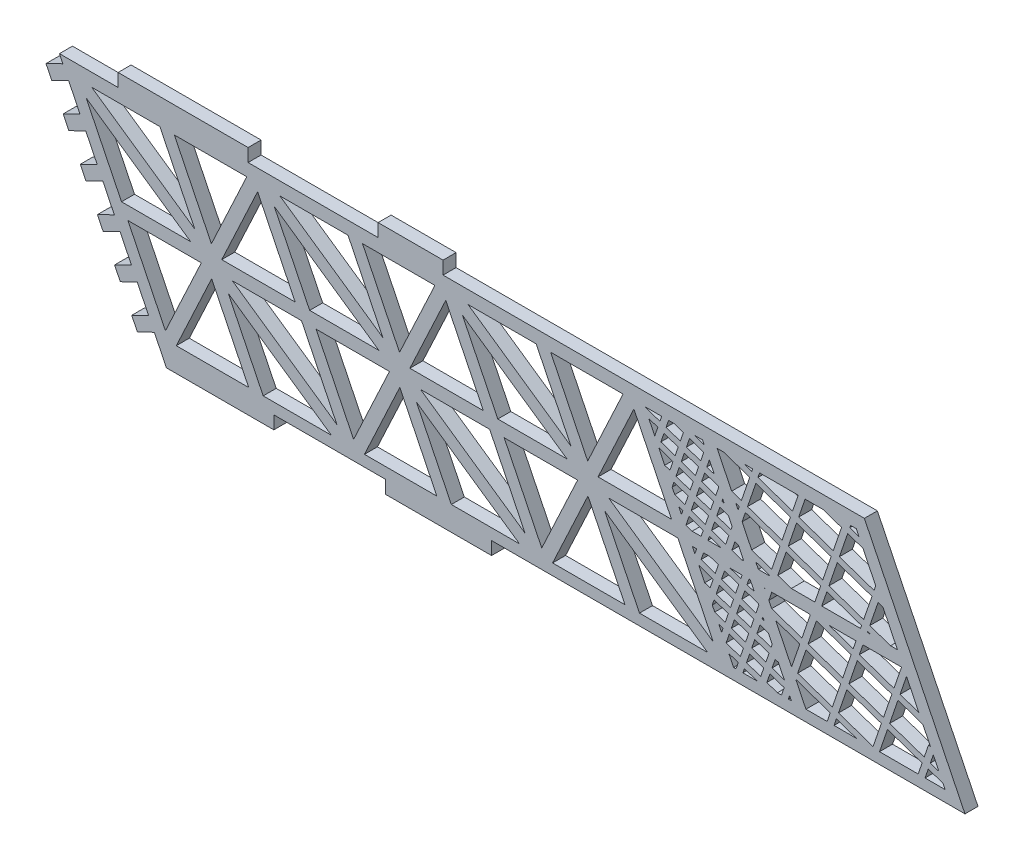
SolidWorks part; units mm, degrees
ref_plane "Front Plane" through (0, 0, 0) normal (0, 0, 1) x (1, 0, 0)
ref_plane "Top Plane" through (0, 0, 0) normal (0, 1, 0) x (1, 0, 0)
ref_plane "Right Plane" through (0, 0, 0) normal (1, 0, 0) x (0, 0, -1)
sketch "Sketch1" plane through (0, 0, 0) normal (0, 0, 1) x (1, 0, 0)
  line L2842 (449.5996, 291) -> (458.5139, 291)
  line L2843 (458.5139, 291) -> (457.1963, 287.1567)
  line L2844 (457.1963, 287.1567) -> (449.2194, 289.8912)
  line L2845 (449.2194, 289.8912) -> (449.5996, 291)
  line L2846 (448.733, 288.4723) -> (456.7099, 285.7377)
  line L2847 (456.7099, 285.7377) -> (454.7887, 280.1333)
  line L2848 (454.7887, 280.1333) -> (446.8118, 282.8678)
  line L2849 (446.8118, 282.8678) -> (448.733, 288.4723)
  line L2850 (444.6261, 281.1177) -> (444.0888, 282.2156)
  line L2851 (444.0888, 282.2156) -> (444.9064, 281.9353)
  line L2852 (444.9064, 281.9353) -> (444.6261, 281.1177)
  line L2853 (445.3928, 283.3542) -> (443.1563, 284.1209)
  line L2854 (443.1563, 284.1209) -> (439.7896, 291)
  line L2855 (439.7896, 291) -> (441.3594, 291)
  line L2856 (441.3594, 291) -> (447.3141, 288.9587)
  line L2857 (447.3141, 288.9587) -> (445.3928, 283.3542)
  line L2858 (448.0139, 291) -> (445.985, 291)
  line L2859 (445.985, 291) -> (447.8005, 290.3776)
  line L2860 (447.8005, 290.3776) -> (448.0139, 291)
  line L2861 (454.3022, 278.7143) -> (452.381, 273.1099)
  line L2862 (452.381, 273.1099) -> (447.772, 274.6898)
  line L2863 (447.772, 274.6898) -> (445.5587, 279.2124)
  line L2864 (445.5587, 279.2124) -> (446.3253, 281.4489)
  line L2865 (446.3253, 281.4489) -> (454.3022, 278.7143)
  line L2866 (478.1923, 256.4128) -> (470.2154, 259.1473)
  line L2867 (470.2154, 259.1473) -> (472.1367, 264.7518)
  line L2868 (472.1367, 264.7518) -> (480.1136, 262.0172)
  line L2869 (480.1136, 262.0172) -> (478.1923, 256.4128)
  line L2870 (480.6, 263.4362) -> (472.6231, 266.1707)
  line L2871 (472.6231, 266.1707) -> (473.4401, 268.5541)
  line L2872 (473.4401, 268.5541) -> (482.3544, 268.5541)
  line L2873 (482.3544, 268.5541) -> (480.6, 263.4362)
  line L2874 (483.5065, 267.289) -> (486.3582, 261.4622)
  line L2875 (486.3582, 261.4622) -> (482.0189, 262.9497)
  line L2876 (482.0189, 262.9497) -> (483.5065, 267.289)
  line L2877 (487.2907, 259.5568) -> (489.0579, 255.9461)
  line L2878 (489.0579, 255.9461) -> (488.5876, 256.1073)
  line L2879 (488.5876, 256.1073) -> (487.5881, 253.1918)
  line L2880 (487.5881, 253.1918) -> (479.6112, 255.9263)
  line L2881 (479.6112, 255.9263) -> (481.5325, 261.5308)
  line L2882 (481.5325, 261.5308) -> (487.2907, 259.5568)
  line L2883 (487.1017, 251.7729) -> (486.1882, 249.1082)
  line L2884 (486.1882, 249.1082) -> (477.2739, 249.1082)
  line L2885 (477.2739, 249.1082) -> (479.1248, 254.5074)
  line L2886 (479.1248, 254.5074) -> (487.1017, 251.7729)
  line L2887 (475.7846, 249.3894) -> (467.8077, 252.1239)
  line L2888 (467.8077, 252.1239) -> (469.729, 257.7284)
  line L2889 (469.729, 257.7284) -> (477.7059, 254.9938)
  line L2890 (477.7059, 254.9938) -> (475.7846, 249.3894)
  line L2891 (474.5443, 271.7752) -> (475.1893, 271.5541)
  line L2892 (475.1893, 271.5541) -> (474.4686, 271.5541)
  line L2893 (474.4686, 271.5541) -> (474.5443, 271.7752)
  line L2894 (476.952, 278.7986) -> (478.0593, 278.419)
  line L2895 (478.0593, 278.419) -> (481.4191, 271.5541)
  line L2896 (481.4191, 271.5541) -> (479.8149, 271.5541)
  line L2897 (479.8149, 271.5541) -> (475.0308, 273.1941)
  line L2898 (475.0308, 273.1941) -> (476.952, 278.7986)
  line L2899 (473.6118, 273.6805) -> (465.6034, 276.4259)
  line L2900 (465.6034, 276.4259) -> (467.5247, 282.0303)
  line L2901 (467.5247, 282.0303) -> (475.5331, 279.285)
  line L2902 (475.5331, 279.285) -> (473.6118, 273.6805)
  line L2903 (472.8829, 271.5541) -> (463.9333, 271.5541)
  line L2904 (463.9333, 271.5541) -> (465.117, 275.0069)
  line L2905 (465.117, 275.0069) -> (473.1254, 272.2616)
  line L2906 (473.1254, 272.2616) -> (472.8829, 271.5541)
  line L2907 (471.2042, 266.6571) -> (465.6706, 268.5541)
  line L2908 (465.6706, 268.5541) -> (471.8544, 268.5541)
  line L2909 (471.8544, 268.5541) -> (471.2042, 266.6571)
  line L2910 (468.7965, 259.6337) -> (460.7881, 262.3791)
  line L2911 (460.7881, 262.3791) -> (462.7093, 267.9835)
  line L2912 (462.7093, 267.9835) -> (470.7177, 265.2382)
  line L2913 (470.7177, 265.2382) -> (468.7965, 259.6337)
  line L2914 (466.3888, 252.6103) -> (458.3804, 255.3557)
  line L2915 (458.3804, 255.3557) -> (460.3016, 260.9601)
  line L2916 (460.3016, 260.9601) -> (468.3101, 258.2148)
  line L2917 (468.3101, 258.2148) -> (466.3888, 252.6103)
  line L2918 (476.3991, 281.8112) -> (473.4436, 287.85)
  line L2919 (473.4436, 287.85) -> (469.9324, 289.0537)
  line L2920 (469.9324, 289.0537) -> (468.0111, 283.4493)
  line L2921 (468.0111, 283.4493) -> (476.0195, 280.7039)
  line L2922 (476.0195, 280.7039) -> (476.3991, 281.8112)
  line L2923 (455.7212, 278.2279) -> (463.6981, 275.4934)
  line L2924 (463.6981, 275.4934) -> (462.3476, 271.5541)
  line L2925 (462.3476, 271.5541) -> (456.9194, 271.5541)
  line L2926 (456.9194, 271.5541) -> (453.7999, 272.6234)
  line L2927 (453.7999, 272.6234) -> (455.7212, 278.2279)
  line L2928 (458.1288, 285.2513) -> (466.1057, 282.5168)
  line L2929 (466.1057, 282.5168) -> (464.1845, 276.9123)
  line L2930 (464.1845, 276.9123) -> (456.2076, 279.6468)
  line L2931 (456.2076, 279.6468) -> (458.1288, 285.2513)
  line L2932 (460.0996, 291) -> (464.2549, 291)
  line L2933 (464.2549, 291) -> (468.5134, 289.5401)
  line L2934 (468.5134, 289.5401) -> (466.5922, 283.9357)
  line L2935 (466.5922, 283.9357) -> (458.6153, 286.6702)
  line L2936 (458.6153, 286.6702) -> (460.0996, 291)
  line L2937 (451.8476, 271.5541) -> (449.3067, 271.5541)
  line L2938 (449.3067, 271.5541) -> (448.7046, 272.7845)
  line L2939 (448.7046, 272.7845) -> (451.8946, 271.6909)
  line L2940 (451.8946, 271.6909) -> (451.8476, 271.5541)
  line L2941 (450.801, 268.5009) -> (450.775, 268.5541)
  line L2942 (450.775, 268.5541) -> (450.8192, 268.5541)
  line L2943 (450.8192, 268.5541) -> (450.801, 268.5009)
  line L2944 (470.5996, 291) -> (471.9019, 291)
  line L2945 (471.9019, 291) -> (472.5111, 289.7554)
  line L2946 (472.5111, 289.7554) -> (470.4188, 290.4727)
  line L2947 (470.4188, 290.4727) -> (470.5996, 291)
  line L2948 (469.0139, 291) -> (468.8805, 291)
  line L2949 (468.8805, 291) -> (468.9998, 290.9591)
  line L2950 (468.9998, 290.9591) -> (469.0139, 291)
  line L2951 (461.045, 268.5541) -> (461.2904, 268.47)
  line L2952 (461.2904, 268.47) -> (459.3691, 262.8655)
  line L2953 (459.3691, 262.8655) -> (452.3878, 265.2588)
  line L2954 (452.3878, 265.2588) -> (451.7335, 266.5956)
  line L2955 (451.7335, 266.5956) -> (452.4049, 268.5541)
  line L2956 (452.4049, 268.5541) -> (461.045, 268.5541)
  line L2957 (456.9759, 255.8841) -> (453.3203, 263.3534)
  line L2958 (453.3203, 263.3534) -> (458.8827, 261.4466)
  line L2959 (458.8827, 261.4466) -> (456.9759, 255.8841)
  line L2960 (471.9794, 249.1082) -> (466.7739, 249.1082)
  line L2961 (466.7739, 249.1082) -> (467.3213, 250.705)
  line L2962 (467.3213, 250.705) -> (471.9794, 249.1082)
  line L2963 (460.2921, 249.1082) -> (457.936, 253.9223)
  line L2964 (457.936, 253.9223) -> (465.9024, 251.1914)
  line L2965 (465.9024, 251.1914) -> (465.1882, 249.1082)
  line L2966 (465.1882, 249.1082) -> (460.2921, 249.1082)
  line L2967 (490.9739, 252.0311) -> (489.0071, 252.7054)
  line L2968 (489.0071, 252.7054) -> (489.6813, 254.6723)
  line L2969 (489.6813, 254.6723) -> (490.9739, 252.0311)
  line L2970 (491.9065, 250.1258) -> (492.4045, 249.1082)
  line L2971 (492.4045, 249.1082) -> (487.7739, 249.1082)
  line L2972 (487.7739, 249.1082) -> (488.5206, 251.2864)
  line L2973 (488.5206, 251.2864) -> (491.9065, 250.1258)
  line L2974 (429.6088, 283.255) -> (428.8914, 281.1623)
  line L2975 (428.8914, 281.1623) -> (427.7052, 281.5689)
  line L2976 (427.7052, 281.5689) -> (426.3299, 284.3791)
  line L2977 (426.3299, 284.3791) -> (429.6088, 283.255)
  line L2978 (427.5337, 287.8908) -> (430.8127, 286.7667)
  line L2979 (430.8127, 286.7667) -> (430.0952, 284.674)
  line L2980 (430.0952, 284.674) -> (426.8163, 285.798)
  line L2981 (426.8163, 285.798) -> (427.5337, 287.8908)
  line L2982 (428.5996, 291) -> (429.9116, 291)
  line L2983 (429.9116, 291) -> (432.0165, 290.2784)
  line L2984 (432.0165, 290.2784) -> (431.2991, 288.1857)
  line L2985 (431.2991, 288.1857) -> (428.0201, 289.3097)
  line L2986 (428.0201, 289.3097) -> (428.5996, 291)
  line L2987 (427.0139, 291) -> (423.0895, 291)
  line L2988 (423.0895, 291) -> (426.6012, 289.7962)
  line L2989 (426.6012, 289.7962) -> (427.0139, 291)
  line L2990 (425.3973, 286.2845) -> (424.022, 289.0946)
  line L2991 (424.022, 289.0946) -> (426.1148, 288.3772)
  line L2992 (426.1148, 288.3772) -> (425.3973, 286.2845)
  line L2993 (429.2666, 271.5541) -> (420.5964, 289.2694)
  line L2994 (420.5964, 289.2694) -> (412.3173, 271.5541)
  line L2995 (412.3173, 271.5541) -> (429.2666, 271.5541)
  line L2996 (429.8239, 279.2569) -> (433.1029, 278.1329)
  line L2997 (433.1029, 278.1329) -> (432.3855, 276.0401)
  line L2998 (432.3855, 276.0401) -> (430.0131, 276.8534)
  line L2999 (430.0131, 276.8534) -> (429.4173, 278.0707)
  line L3000 (429.4173, 278.0707) -> (429.8239, 279.2569)
  line L3001 (431.0278, 282.7686) -> (434.3067, 281.6446)
  line L3002 (434.3067, 281.6446) -> (433.5893, 279.5518)
  line L3003 (433.5893, 279.5518) -> (430.3104, 280.6759)
  line L3004 (430.3104, 280.6759) -> (431.0278, 282.7686)
  line L3005 (432.2316, 286.2803) -> (435.5106, 285.1563)
  line L3006 (435.5106, 285.1563) -> (434.7932, 283.0635)
  line L3007 (434.7932, 283.0635) -> (431.5142, 284.1876)
  line L3008 (431.5142, 284.1876) -> (432.2316, 286.2803)
  line L3009 (433.4354, 289.792) -> (436.7144, 288.668)
  line L3010 (436.7144, 288.668) -> (435.997, 286.5752)
  line L3011 (435.997, 286.5752) -> (432.718, 287.6993)
  line L3012 (432.718, 287.6993) -> (433.4354, 289.792)
  line L3013 (433.318, 274.1347) -> (436.597, 273.0107)
  line L3014 (436.597, 273.0107) -> (436.0976, 271.5541)
  line L3015 (436.0976, 271.5541) -> (434.0238, 271.5541)
  line L3016 (434.0238, 271.5541) -> (432.6006, 272.042)
  line L3017 (432.6006, 272.042) -> (433.318, 274.1347)
  line L3018 (434.5218, 277.6464) -> (437.8008, 276.5224)
  line L3019 (437.8008, 276.5224) -> (437.0834, 274.4296)
  line L3020 (437.0834, 274.4296) -> (433.8044, 275.5537)
  line L3021 (433.8044, 275.5537) -> (434.5218, 277.6464)
  line L3022 (435.7257, 281.1581) -> (439.0047, 280.0341)
  line L3023 (439.0047, 280.0341) -> (438.2872, 277.9413)
  line L3024 (438.2872, 277.9413) -> (435.0083, 279.0654)
  line L3025 (435.0083, 279.0654) -> (435.7257, 281.1581)
  line L3026 (436.9295, 284.6698) -> (440.0755, 283.5914)
  line L3027 (440.0755, 283.5914) -> (440.1629, 283.4128)
  line L3028 (440.1629, 283.4128) -> (439.4911, 281.453)
  line L3029 (439.4911, 281.453) -> (436.2121, 282.5771)
  line L3030 (436.2121, 282.5771) -> (436.9295, 284.6698)
  line L3031 (438.008, 287.8158) -> (439.143, 285.4967)
  line L3032 (439.143, 285.4967) -> (437.4159, 286.0888)
  line L3033 (437.4159, 286.0888) -> (438.008, 287.8158)
  line L3034 (431.5722, 273.6677) -> (430.9456, 274.948)
  line L3035 (430.9456, 274.948) -> (431.8991, 274.6212)
  line L3036 (431.8991, 274.6212) -> (431.5722, 273.6677)
  line L3037 (438.9029, 251.8647) -> (430.7348, 268.5541)
  line L3038 (430.7348, 268.5541) -> (414.7672, 268.5541)
  line L3039 (414.7672, 268.5541) -> (438.9029, 251.8647)
  line L3040 (435.6082, 265.5009) -> (438.8872, 264.3768)
  line L3041 (438.8872, 264.3768) -> (438.1698, 262.284)
  line L3042 (438.1698, 262.284) -> (436.9366, 262.7068)
  line L3043 (436.9366, 262.7068) -> (435.5921, 265.4539)
  line L3044 (435.5921, 265.4539) -> (435.6082, 265.5009)
  line L3045 (436.6549, 268.5541) -> (438.1495, 268.5541)
  line L3046 (438.1495, 268.5541) -> (440.091, 267.8885)
  line L3047 (440.091, 267.8885) -> (439.3736, 265.7957)
  line L3048 (439.3736, 265.7957) -> (436.0947, 266.9198)
  line L3049 (436.0947, 266.9198) -> (436.6549, 268.5541)
  line L3050 (438.0159, 272.5243) -> (440.846, 271.5541)
  line L3051 (440.846, 271.5541) -> (437.6833, 271.5541)
  line L3052 (437.6833, 271.5541) -> (438.0159, 272.5243)
  line L3053 (439.2198, 276.036) -> (442.4987, 274.9119)
  line L3054 (442.4987, 274.9119) -> (441.7813, 272.8191)
  line L3055 (441.7813, 272.8191) -> (438.5023, 273.9432)
  line L3056 (438.5023, 273.9432) -> (439.2198, 276.036)
  line L3057 (440.4236, 279.5477) -> (442.3833, 278.8758)
  line L3058 (442.3833, 278.8758) -> (443.2503, 277.1044)
  line L3059 (443.2503, 277.1044) -> (442.9852, 276.3308)
  line L3060 (442.9852, 276.3308) -> (439.7062, 277.4549)
  line L3061 (439.7062, 277.4549) -> (440.4236, 279.5477)
  line L3062 (441.0954, 281.5074) -> (441.4508, 280.7812)
  line L3063 (441.4508, 280.7812) -> (440.91, 280.9666)
  line L3064 (440.91, 280.9666) -> (441.0954, 281.5074)
  line L3065 (434.6757, 267.4062) -> (434.6288, 267.4223)
  line L3066 (434.6288, 267.4223) -> (434.0749, 268.5541)
  line L3067 (434.0749, 268.5541) -> (435.0692, 268.5541)
  line L3068 (435.0692, 268.5541) -> (434.6757, 267.4062)
  line L3069 (439.1023, 260.3787) -> (442.3813, 259.2546)
  line L3070 (442.3813, 259.2546) -> (441.6639, 257.1619)
  line L3071 (441.6639, 257.1619) -> (439.2445, 257.9912)
  line L3072 (439.2445, 257.9912) -> (438.6796, 259.1455)
  line L3073 (438.6796, 259.1455) -> (439.1023, 260.3787)
  line L3074 (440.3062, 263.8904) -> (443.5851, 262.7663)
  line L3075 (443.5851, 262.7663) -> (442.8677, 260.6736)
  line L3076 (442.8677, 260.6736) -> (439.5887, 261.7976)
  line L3077 (439.5887, 261.7976) -> (440.3062, 263.8904)
  line L3078 (441.51, 267.4021) -> (444.789, 266.278)
  line L3079 (444.789, 266.278) -> (444.0715, 264.1853)
  line L3080 (444.0715, 264.1853) -> (440.7926, 265.3093)
  line L3081 (440.7926, 265.3093) -> (441.51, 267.4021)
  line L3082 (443.9177, 274.4255) -> (444.6912, 274.1603)
  line L3083 (444.6912, 274.1603) -> (445.9667, 271.5541)
  line L3084 (445.9667, 271.5541) -> (445.4716, 271.5541)
  line L3085 (445.4716, 271.5541) -> (443.2003, 272.3327)
  line L3086 (443.2003, 272.3327) -> (443.9177, 274.4255)
  line L3087 (442.5964, 255.2565) -> (445.8754, 254.1324)
  line L3088 (445.8754, 254.1324) -> (445.1579, 252.0397)
  line L3089 (445.1579, 252.0397) -> (441.879, 253.1637)
  line L3090 (441.879, 253.1637) -> (442.5964, 255.2565)
  line L3091 (443.8002, 258.7682) -> (447.0792, 257.6441)
  line L3092 (447.0792, 257.6441) -> (446.3618, 255.5514)
  line L3093 (446.3618, 255.5514) -> (443.0828, 256.6754)
  line L3094 (443.0828, 256.6754) -> (443.8002, 258.7682)
  line L3095 (445.0041, 262.2799) -> (448.283, 261.1558)
  line L3096 (448.283, 261.1558) -> (447.5656, 259.0631)
  line L3097 (447.5656, 259.0631) -> (444.2867, 260.1871)
  line L3098 (444.2867, 260.1871) -> (445.0041, 262.2799)
  line L3099 (446.2079, 265.7916) -> (449.3069, 264.7292)
  line L3100 (449.3069, 264.7292) -> (449.4252, 264.4876)
  line L3101 (449.4252, 264.4876) -> (448.7695, 262.5748)
  line L3102 (448.7695, 262.5748) -> (445.4905, 263.6988)
  line L3103 (445.4905, 263.6988) -> (446.2079, 265.7916)
  line L3104 (447.1549, 268.5541) -> (447.435, 268.5541)
  line L3105 (447.435, 268.5541) -> (448.3744, 266.6346)
  line L3106 (448.3744, 266.6346) -> (446.6943, 267.2105)
  line L3107 (446.6943, 267.2105) -> (447.1549, 268.5541)
  line L3108 (445.2754, 267.697) -> (442.7751, 268.5541)
  line L3109 (442.7751, 268.5541) -> (445.5692, 268.5541)
  line L3110 (445.5692, 268.5541) -> (445.2754, 267.697)
  line L3111 (440.8345, 254.7425) -> (440.177, 256.0859)
  line L3112 (440.177, 256.0859) -> (441.1774, 255.7429)
  line L3113 (441.1774, 255.7429) -> (440.8345, 254.7425)
  line L3114 (445.7387, 249.1082) -> (449.0839, 249.1082)
  line L3115 (449.0839, 249.1082) -> (446.0905, 250.1343)
  line L3116 (446.0905, 250.1343) -> (445.7387, 249.1082)
  line L3117 (447.2943, 253.646) -> (450.5733, 252.522)
  line L3118 (450.5733, 252.522) -> (449.8559, 250.4292)
  line L3119 (449.8559, 250.4292) -> (446.5769, 251.5533)
  line L3120 (446.5769, 251.5533) -> (447.2943, 253.646)
  line L3121 (448.4981, 257.1577) -> (451.7771, 256.0337)
  line L3122 (451.7771, 256.0337) -> (451.0597, 253.9409)
  line L3123 (451.0597, 253.9409) -> (447.7807, 255.065)
  line L3124 (447.7807, 255.065) -> (448.4981, 257.1577)
  line L3125 (449.702, 260.6694) -> (451.6148, 260.0137)
  line L3126 (451.6148, 260.0137) -> (452.5126, 258.1792)
  line L3127 (452.5126, 258.1792) -> (452.2635, 257.4526)
  line L3128 (452.2635, 257.4526) -> (448.9846, 258.5767)
  line L3129 (448.9846, 258.5767) -> (449.702, 260.6694)
  line L3130 (450.3577, 262.5822) -> (450.6823, 261.9191)
  line L3131 (450.6823, 261.9191) -> (450.1884, 262.0883)
  line L3132 (450.1884, 262.0883) -> (450.3577, 262.5822)
  line L3133 (443.592, 249.1082) -> (442.4849, 251.3703)
  line L3134 (442.4849, 251.3703) -> (444.6715, 250.6207)
  line L3135 (444.6715, 250.6207) -> (444.153, 249.1082)
  line L3136 (444.153, 249.1082) -> (443.592, 249.1082)
  line L3137 (451.9922, 252.0355) -> (455.2712, 250.9115)
  line L3138 (455.2712, 250.9115) -> (454.653, 249.1082)
  line L3139 (454.653, 249.1082) -> (453.7095, 249.1082)
  line L3140 (453.7095, 249.1082) -> (451.2748, 249.9428)
  line L3141 (451.2748, 249.9428) -> (451.9922, 252.0355)
  line L3142 (453.1961, 255.5472) -> (453.9226, 255.2982)
  line L3143 (453.9226, 255.2982) -> (455.298, 252.488)
  line L3144 (455.298, 252.488) -> (452.4786, 253.4545)
  line L3145 (452.4786, 253.4545) -> (453.1961, 255.5472)
  line L3146 (456.9521, 249.1082) -> (456.2387, 249.1082)
  line L3147 (456.2387, 249.1082) -> (456.5326, 249.9654)
  line L3148 (456.5326, 249.9654) -> (456.9521, 249.1082)
  line L3149 (434.5372, 291) -> (436.4496, 291)
  line L3150 (436.4496, 291) -> (436.8351, 290.2123)
  line L3151 (436.8351, 290.2123) -> (434.5372, 291)
  line L3152 (295.4659, 291) -> (311.1987, 291)
  line L3153 (311.1987, 291) -> (319.2466, 274.5561)
  line L3154 (319.2466, 274.5561) -> (295.4659, 291)
  line L3155 (294.1777, 288.2434) -> (302.3457, 271.5541)
  line L3156 (302.3457, 271.5541) -> (318.3134, 271.5541)
  line L3157 (318.3134, 271.5541) -> (294.1777, 288.2434)
  line L3158 (343.8943, 268.5541) -> (352.0623, 251.8647)
  line L3159 (352.0623, 251.8647) -> (327.9266, 268.5541)
  line L3160 (327.9266, 268.5541) -> (343.8943, 268.5541)
  line L3161 (335.0413, 249.1082) -> (326.9934, 265.552)
  line L3162 (326.9934, 265.552) -> (350.774, 249.1082)
  line L3163 (350.774, 249.1082) -> (335.0413, 249.1082)
  line L3164 (345.766, 271.5541) -> (337.598, 288.2434)
  line L3165 (337.598, 288.2434) -> (361.7337, 271.5541)
  line L3166 (361.7337, 271.5541) -> (345.766, 271.5541)
  line L3167 (354.619, 291) -> (362.6669, 274.5561)
  line L3168 (362.6669, 274.5561) -> (338.8862, 291)
  line L3169 (338.8862, 291) -> (354.619, 291)
  line L3170 (387.3146, 268.5541) -> (395.4826, 251.8647)
  line L3171 (395.4826, 251.8647) -> (371.3469, 268.5541)
  line L3172 (371.3469, 268.5541) -> (387.3146, 268.5541)
  line L3173 (378.4616, 249.1082) -> (370.4137, 265.552)
  line L3174 (370.4137, 265.552) -> (394.1943, 249.1082)
  line L3175 (394.1943, 249.1082) -> (378.4616, 249.1082)
  line L3176 (389.1863, 271.5541) -> (381.0183, 288.2434)
  line L3177 (381.0183, 288.2434) -> (405.154, 271.5541)
  line L3178 (405.154, 271.5541) -> (389.1863, 271.5541)
  line L3179 (398.0393, 291) -> (406.0872, 274.5561)
  line L3180 (406.0872, 274.5561) -> (382.3065, 291)
  line L3181 (382.3065, 291) -> (398.0393, 291)
  line L3182 (401.8274, 249.1082) -> (409.9918, 266.578)
  line L3183 (409.9918, 266.578) -> (418.5418, 249.1082)
  line L3184 (418.5418, 249.1082) -> (401.8274, 249.1082)
  line L3185 (312.4842, 250.8387) -> (303.814, 268.5541)
  line L3186 (303.814, 268.5541) -> (320.7633, 268.5541)
  line L3187 (320.7633, 268.5541) -> (312.4842, 250.8387)
  line L3188 (333.7558, 289.2694) -> (342.426, 271.5541)
  line L3189 (342.426, 271.5541) -> (325.4767, 271.5541)
  line L3190 (325.4767, 271.5541) -> (333.7558, 289.2694)
  line L3191 (314.9869, 249.1082) -> (331.7013, 249.1082)
  line L3192 (331.7013, 249.1082) -> (323.1512, 266.578)
  line L3193 (323.1512, 266.578) -> (314.9869, 249.1082)
  line L3194 (331.2531, 291) -> (314.5387, 291)
  line L3195 (314.5387, 291) -> (323.0888, 273.5301)
  line L3196 (323.0888, 273.5301) -> (331.2531, 291)
  line L3197 (355.9045, 250.8387) -> (347.2343, 268.5541)
  line L3198 (347.2343, 268.5541) -> (364.1836, 268.5541)
  line L3199 (364.1836, 268.5541) -> (355.9045, 250.8387)
  line L3200 (358.4071, 249.1082) -> (375.1216, 249.1082)
  line L3201 (375.1216, 249.1082) -> (366.5715, 266.578)
  line L3202 (366.5715, 266.578) -> (358.4071, 249.1082)
  line L3203 (377.1761, 289.2694) -> (385.8463, 271.5541)
  line L3204 (385.8463, 271.5541) -> (368.897, 271.5541)
  line L3205 (368.897, 271.5541) -> (377.1761, 289.2694)
  line L3206 (374.6734, 291) -> (357.959, 291)
  line L3207 (357.959, 291) -> (366.5091, 273.5301)
  line L3208 (366.5091, 273.5301) -> (374.6734, 291)
  line L3209 (399.3248, 250.8387) -> (390.6546, 268.5541)
  line L3210 (390.6546, 268.5541) -> (407.6039, 268.5541)
  line L3211 (407.6039, 268.5541) -> (399.3248, 250.8387)
  line L3212 (418.0937, 291) -> (401.3793, 291)
  line L3213 (401.3793, 291) -> (409.9294, 273.5301)
  line L3214 (409.9294, 273.5301) -> (418.0937, 291)
  line L3215 (421.8819, 249.1082) -> (413.834, 265.552)
  line L3216 (413.834, 265.552) -> (437.6146, 249.1082)
  line L3217 (437.6146, 249.1082) -> (421.8819, 249.1082)
  line L3218 (312.7148, 243.5429) -> (337.4966, 243.5429)
  line L3219 (337.4966, 243.5429) -> (337.4966, 246.5429)
  line L3220 (337.4966, 246.5429) -> (363.2966, 246.5429)
  line L3221 (363.2966, 246.5429) -> (363.2966, 243.5429)
  line L3222 (363.2966, 243.5429) -> (387.7466, 243.5429)
  line L3223 (387.7466, 243.5429) -> (387.7466, 246.5429)
  line L3224 (387.7466, 246.5429) -> (497, 246.5429)
  line L3225 (497, 246.5429) -> (473.7737, 294)
  line L3226 (473.7737, 294) -> (376.5521, 294)
  line L3227 (376.5521, 294) -> (376.5521, 297)
  line L3228 (376.5521, 297) -> (361.5521, 297)
  line L3229 (361.5521, 297) -> (361.5521, 294)
  line L3230 (361.5521, 294) -> (331.5521, 294)
  line L3231 (331.5521, 294) -> (331.5521, 297)
  line L3232 (331.5521, 297) -> (301.5521, 297)
  line L3233 (301.5521, 297) -> (301.5521, 294)
  line L3234 (301.5521, 294) -> (288.0203, 294)
  line L3235 (288.0203, 294) -> (288.8185, 292.3691)
  line L3236 (288.8185, 292.3691) -> (284.9193, 290.4608)
  line L3237 (284.9193, 290.4608) -> (286.2381, 287.7662)
  line L3238 (286.2381, 287.7662) -> (290.1373, 289.6745)
  line L3239 (290.1373, 289.6745) -> (292.7748, 284.2853)
  line L3240 (292.7748, 284.2853) -> (288.8756, 282.377)
  line L3241 (288.8756, 282.377) -> (290.1944, 279.6824)
  line L3242 (290.1944, 279.6824) -> (294.0936, 281.5907)
  line L3243 (294.0936, 281.5907) -> (296.7312, 276.2016)
  line L3244 (296.7312, 276.2016) -> (292.8319, 274.2932)
  line L3245 (292.8319, 274.2932) -> (294.1507, 271.5986)
  line L3246 (294.1507, 271.5986) -> (298.0499, 273.507)
  line L3247 (298.0499, 273.507) -> (300.6875, 268.1178)
  line L3248 (300.6875, 268.1178) -> (296.7883, 266.2094)
  line L3249 (296.7883, 266.2094) -> (298.1071, 263.5149)
  line L3250 (298.1071, 263.5149) -> (302.0063, 265.4232)
  line L3251 (302.0063, 265.4232) -> (304.6438, 260.034)
  line L3252 (304.6438, 260.034) -> (300.7446, 258.1257)
  line L3253 (300.7446, 258.1257) -> (302.0634, 255.4311)
  line L3254 (302.0634, 255.4311) -> (305.9626, 257.3394)
  line L3255 (305.9626, 257.3394) -> (308.6001, 251.9502)
  line L3256 (308.6001, 251.9502) -> (304.7009, 250.0419)
  line L3257 (304.7009, 250.0419) -> (306.0197, 247.3473)
  line L3258 (306.0197, 247.3473) -> (309.9189, 249.2556)
  line L3259 (309.9189, 249.2556) -> (312.7148, 243.5429)
extrude "Boss-Extrude1" add sketch "Sketch1" along normal blind 3 contours L3258 L3259 L3218 L3219 L3220 L3221 L3222 L3223 L3224 L3225 L3226 L3227 L3228 L3229 L3230 L3231 L3232 L3233 L3234 L3235 L3236 L3237 L3238 L3239 L3240 L3241 L3242 L3243 L3244 L3245 L3246 L3247 L3248 L3249 L3250 L3251 L3252 L3253 L3254 L3255 L3256 L3257 L3216 L3217 L3215 L3214 L3213 L3212
